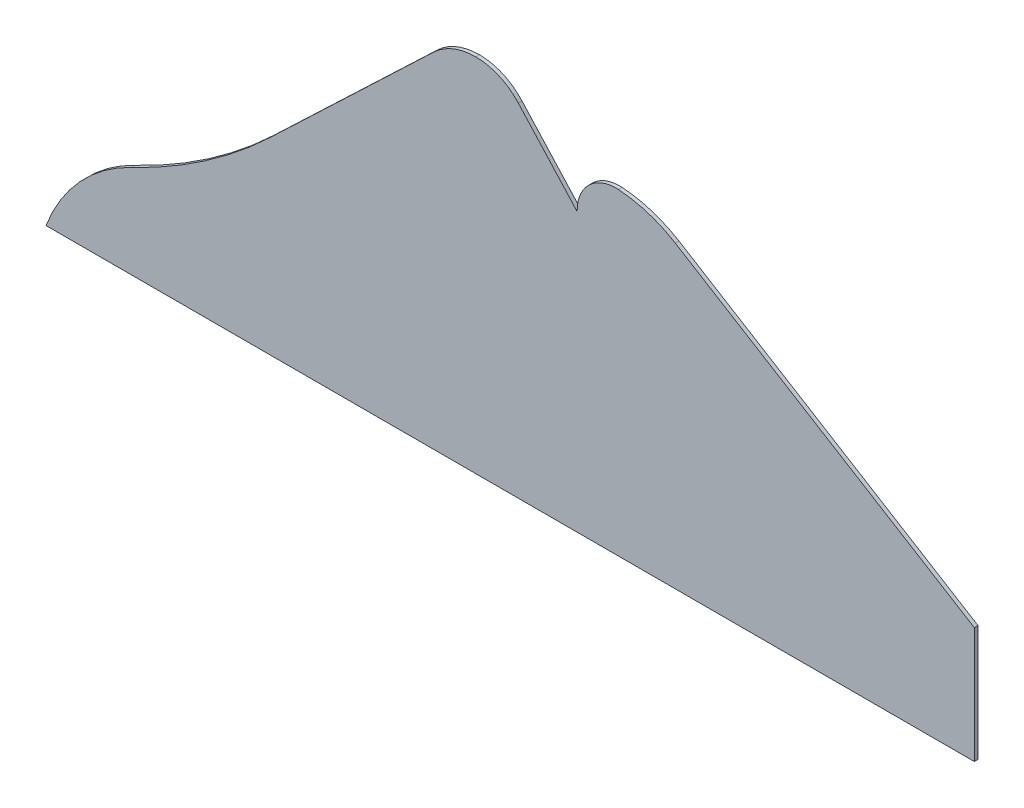
SolidWorks part; units mm, degrees
material "Acrylic (Medium-high impact)"
ref_plane "Front Plane" through (0, 0, 0) normal (0, 0, 1) x (1, 0, 0)
ref_plane "Top Plane" through (0, 0, 0) normal (0, 1, 0) x (1, 0, 0)
ref_plane "Right Plane" through (0, 0, 0) normal (1, 0, 0) x (0, 0, -1)
sketch "Sketch1" plane through (0, 0, 0) normal (0, 0, 1) x (1, 0, 0)
  line L1 (0, 0) -> (800.1, 0)
  line L2 (0, 0) -> (0, 311.15)
  line L3 (0, 311.15) -> (800.1, 311.15)
  line L4 (800.1, 0) -> (800.1, 311.15)
  dimension "D1" = 311.15
  dimension "D2" = 800.1
extrude "Boss-Extrude1" add sketch "Sketch1" along normal mid plane 3.175
sketch "Sketch2" plane through (0, 0, 1.5875) normal (0, 0, 1) x (1, 0, 0)
  line L0 (193.4504, 162.6213) -> (334.2791, 296.6799)
  line L1 (800.1, 311.15) -> (0, 311.15) construction
  line L2 (407.1057, 294.9626) -> (457.8166, 239.285)
  line L3 (542.4482, 258.0437) -> (800.1, 99.9416)
  line L4 (800.1, 0) -> (800.1, 311.15) construction
  line L5 (370.467, 311.15) -> (0, 311.15)
  line L6 (0, 311.15) -> (0, 0)
  line L7 (800.1, 99.9416) -> (800.1, 311.15)
  line L8 (800.1, 311.15) -> (370.467, 311.15)
  arc A0 (0, 0) -> (73.7997, 80.2885) centre (136.5807, -51.4806) cw
  arc A1 (73.7997, 80.2885) -> (193.4504, 162.6213) centre (-124.6286, 496.7637) ccw
  arc A2 (334.2791, 296.6799) -> (370.467, 311.15) centre (370.467, 258.6645) cw
  arc A3 (370.467, 311.15) -> (407.1057, 294.9626) centre (370.467, 261.5921) cw
  arc A4 (457.8166, 239.285) -> (493.303, 273.601) centre (491.2073, 240.2618) cw
  arc A5 (493.303, 273.601) -> (542.4482, 258.0437) centre (486.6046, 167.0378) cw
extrude "Cut-Extrude1" cut sketch "Sketch2" against normal through all contours A4 A5 L3 L4 L6 A3 L2 | L0 A2 L6 L5 A0 A1
